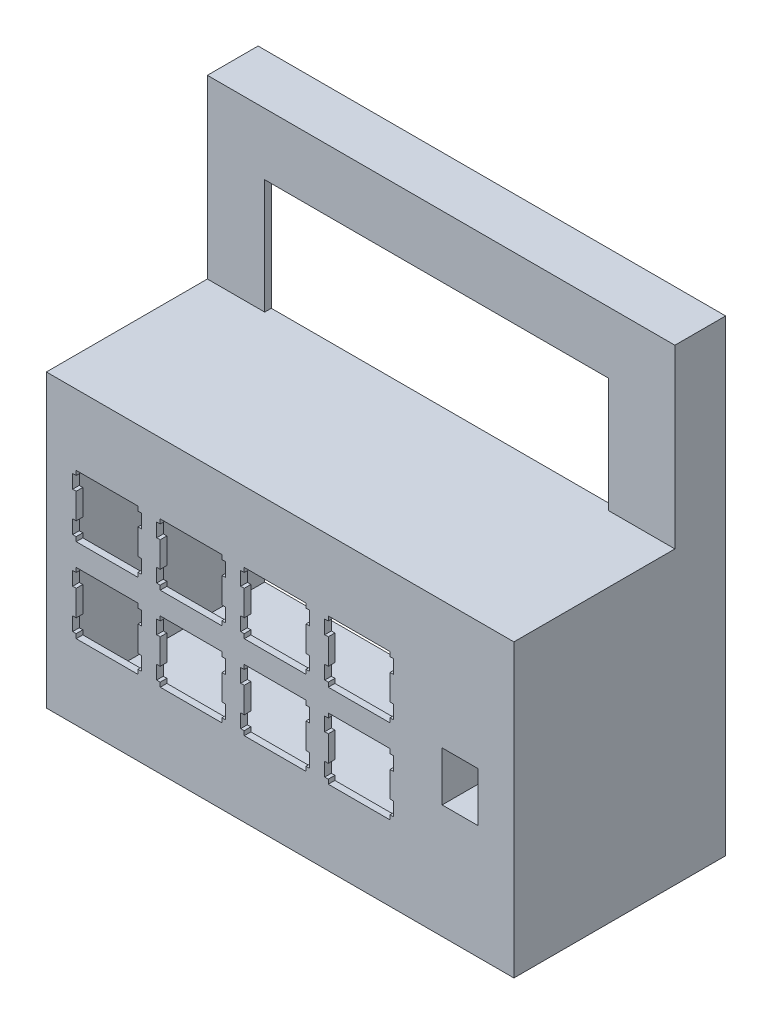
SolidWorks part; units mm, degrees
ref_plane "前视基准面" through (0, 0, 0) normal (0, 0, 1) x (1, 0, 0)
ref_plane "上视基准面" through (0, 0, 0) normal (0, 1, 0) x (1, 0, 0)
ref_plane "右视基准面" through (0, 0, 0) normal (1, 0, 0) x (0, 0, -1)
sketch "草图1" plane through (0, 0, 0) normal (0, 0, 1) x (1, 0, 0)
  line L11 (0, 0) -> (0, -40)
  line L12 (0, -40) -> (106, -40)
  line L13 (106, -40) -> (106, 0)
  line L14 (106, 0) -> (0, 0)
extrude "凸台-拉伸1" add sketch "草图1" along normal blind 1.5
sketch "草图5" plane through (0, -40, 0) normal (0, -1, 0) x (1, 0, 0)
  line L0 (0, 0) -> (106, 0)
  line L1 (106, 0) -> (106, 36.5)
  line L2 (106, 36.5) -> (0, 36.5)
  line L3 (0, 36.5) -> (0, 0)
extrude "凸台-拉伸4" add sketch "草图5" along normal blind 1.5
sketch "草图6" plane through (0, 0, 36.5) normal (0, 0, 1) x (1, 0, 0)
  line L0 (0, -40) -> (0, -106)
  line L1 (0, -106) -> (106, -106)
  line L2 (106, -106) -> (106, -40)
  line L3 (106, -40) -> (0, -40)
extrude "凸台-拉伸5" add sketch "草图6" along normal blind 1.5
sketch "草图7" plane through (0, 0, 0) normal (0, 0, -1) x (-1, 0, 0)
  line L0 (-106, -41.5) -> (-106, 0)
  line L1 (-106, 0) -> (0, 0)
  line L2 (0, 0) -> (0, -41.5)
  line L3 (0, -41.5) -> (-1.5, -41.5)
  line L4 (0, -41.5) -> (-106, -41.5) construction
  line L5 (-1.5, -41.5) -> (-1.5, -1.5)
  line L6 (-1.5, -1.5) -> (-104.5, -1.5)
  line L7 (-104.5, -1.5) -> (-104.5, -41.5)
  line L8 (-104.5, -41.5) -> (-106, -41.5)
extrude "凸台-拉伸6" add sketch "草图7" along normal blind 10
sketch "草图8" plane through (0, 0, 36.5) normal (0, 0, -1) x (-1, 0, 0)
  line L0 (-106, -41.5) -> (-106, -106)
  line L1 (-106, -106) -> (0, -106)
  line L2 (0, -106) -> (0, -41.5)
  line L3 (0, -41.5) -> (-1.5, -41.5)
  line L4 (-106, -41.5) -> (0, -41.5) construction
  line L5 (-1.5, -41.5) -> (-1.5, -104.5)
  line L6 (-1.5, -104.5) -> (-104.5, -104.5)
  line L7 (-104.5, -104.5) -> (-104.5, -41.5)
  line L8 (-104.5, -41.5) -> (-106, -41.5)
extrude "凸台-拉伸7" add sketch "草图8" along normal blind 46.5
sketch "草图11" plane through (0, 0, 38) normal (0, 0, 1) x (1, 0, 0)
  line L0 (63.9112, -74.9976) -> (63.9112, -75.9981)
  line L1 (63.9112, -75.9981) -> (63.1104, -75.9981)
  line L2 (63.1104, -75.9981) -> (63.1104, -79.0973)
  line L3 (63.1104, -79.0973) -> (63.9112, -79.0973)
  line L4 (63.9112, -79.0973) -> (63.9112, -84.8973)
  line L5 (63.9112, -84.8973) -> (63.1104, -84.8973)
  line L6 (63.1104, -84.8973) -> (63.1104, -87.9979)
  line L7 (63.1104, -87.9979) -> (63.9112, -87.9979)
  line L8 (63.9112, -87.9979) -> (63.9112, -88.9983)
  line L9 (63.9112, -88.9983) -> (77.9105, -88.9983)
  line L10 (77.9105, -88.9983) -> (77.9105, -87.9979)
  line L11 (77.9105, -87.9979) -> (78.7113, -87.9979)
  line L12 (78.7113, -87.9979) -> (78.7113, -84.8973)
  line L13 (78.7113, -84.8973) -> (77.9105, -84.8973)
  line L14 (77.9105, -84.8973) -> (77.9105, -79.0973)
  line L15 (77.9105, -79.0973) -> (78.7113, -79.0973)
  line L16 (78.7113, -79.0973) -> (78.7113, -75.9981)
  line L17 (78.7113, -75.9981) -> (77.9105, -75.9981)
  line L18 (77.9105, -75.9981) -> (77.9105, -74.9976)
  line L19 (77.9105, -74.9976) -> (63.9112, -74.9976)
  line L20 (44.8612, -74.9976) -> (44.8612, -75.9981)
  line L21 (44.8612, -75.9981) -> (44.0604, -75.9981)
  line L22 (44.0604, -75.9981) -> (44.0604, -79.0973)
  line L23 (44.0604, -79.0973) -> (44.8612, -79.0973)
  line L24 (44.8612, -79.0973) -> (44.8612, -84.8973)
  line L25 (44.8612, -84.8973) -> (44.0604, -84.8973)
  line L26 (44.0604, -84.8973) -> (44.0604, -87.9979)
  line L27 (44.0604, -87.9979) -> (44.8612, -87.9979)
  line L28 (44.8612, -87.9979) -> (44.8612, -88.9983)
  line L29 (44.8612, -88.9983) -> (58.8605, -88.9983)
  line L30 (58.8605, -88.9983) -> (58.8605, -87.9979)
  line L31 (58.8605, -87.9979) -> (59.6613, -87.9979)
  line L32 (59.6613, -87.9979) -> (59.6613, -84.8973)
  line L33 (59.6613, -84.8973) -> (58.8605, -84.8973)
  line L34 (58.8605, -84.8973) -> (58.8605, -79.0973)
  line L35 (58.8605, -79.0973) -> (59.6613, -79.0973)
  line L36 (59.6613, -79.0973) -> (59.6613, -75.9981)
  line L37 (59.6613, -75.9981) -> (58.8605, -75.9981)
  line L38 (58.8605, -75.9981) -> (58.8605, -74.9976)
  line L39 (58.8605, -74.9976) -> (44.8612, -74.9976)
  line L40 (25.8112, -74.9976) -> (25.8112, -75.9981)
  line L41 (25.8112, -75.9981) -> (25.0105, -75.9981)
  line L42 (25.0105, -75.9981) -> (25.0105, -79.0973)
  line L43 (25.0105, -79.0973) -> (25.8112, -79.0973)
  line L44 (25.8112, -79.0973) -> (25.8112, -84.8973)
  line L45 (25.8112, -84.8973) -> (25.0105, -84.8973)
  line L46 (25.0105, -84.8973) -> (25.0105, -87.9979)
  line L47 (25.0105, -87.9979) -> (25.8112, -87.9979)
  line L48 (25.8112, -87.9979) -> (25.8112, -88.9983)
  line L49 (25.8112, -88.9983) -> (39.8105, -88.9983)
  line L50 (39.8105, -88.9983) -> (39.8105, -87.9979)
  line L51 (39.8105, -87.9979) -> (40.6113, -87.9979)
  line L52 (40.6113, -87.9979) -> (40.6113, -84.8973)
  line L53 (40.6113, -84.8973) -> (39.8105, -84.8973)
  line L54 (39.8105, -84.8973) -> (39.8105, -79.0973)
  line L55 (39.8105, -79.0973) -> (40.6113, -79.0973)
  line L56 (40.6113, -79.0973) -> (40.6113, -75.9981)
  line L57 (40.6113, -75.9981) -> (39.8105, -75.9981)
  line L58 (39.8105, -75.9981) -> (39.8105, -74.9976)
  line L59 (39.8105, -74.9976) -> (25.8112, -74.9976)
  line L60 (6.7612, -74.9976) -> (6.7612, -75.9981)
  line L61 (6.7612, -75.9981) -> (5.9605, -75.9981)
  line L62 (5.9605, -75.9981) -> (5.9605, -79.0973)
  line L63 (5.9605, -79.0973) -> (6.7612, -79.0973)
  line L64 (6.7612, -79.0973) -> (6.7612, -84.8973)
  line L65 (6.7612, -84.8973) -> (5.9605, -84.8973)
  line L66 (5.9605, -84.8973) -> (5.9605, -87.9979)
  line L67 (5.9605, -87.9979) -> (6.7612, -87.9979)
  line L68 (6.7612, -87.9979) -> (6.7612, -88.9983)
  line L69 (6.7612, -88.9983) -> (20.7607, -88.9983)
  line L70 (20.7607, -88.9983) -> (20.7607, -87.9979)
  line L71 (20.7607, -87.9979) -> (21.5613, -87.9979)
  line L72 (21.5613, -87.9979) -> (21.5613, -84.8973)
  line L73 (21.5613, -84.8973) -> (20.7607, -84.8973)
  line L74 (20.7607, -84.8973) -> (20.7607, -79.0973)
  line L75 (20.7607, -79.0973) -> (21.5613, -79.0973)
  line L76 (21.5613, -79.0973) -> (21.5613, -75.9981)
  line L77 (21.5613, -75.9981) -> (20.7607, -75.9981)
  line L78 (20.7607, -75.9981) -> (20.7607, -74.9976)
  line L79 (20.7607, -74.9976) -> (6.7612, -74.9976)
  line L80 (63.9112, -55.949) -> (63.9112, -56.9495)
  line L81 (63.9112, -56.9495) -> (63.1104, -56.9495)
  line L82 (63.1104, -56.9495) -> (63.1104, -60.0487)
  line L83 (63.1104, -60.0487) -> (63.9112, -60.0487)
  line L84 (63.9112, -60.0487) -> (63.9112, -65.8487)
  line L85 (63.9112, -65.8487) -> (63.1104, -65.8487)
  line L86 (63.1104, -65.8487) -> (63.1104, -68.9493)
  line L87 (63.1104, -68.9493) -> (63.9112, -68.9493)
  line L88 (63.9112, -68.9493) -> (63.9112, -69.9483)
  line L89 (63.9112, -69.9483) -> (77.9105, -69.9483)
  line L90 (77.9105, -69.9483) -> (77.9105, -68.9493)
  line L91 (77.9105, -68.9493) -> (78.7113, -68.9493)
  line L92 (78.7113, -68.9493) -> (78.7113, -65.8487)
  line L93 (78.7113, -65.8487) -> (77.9105, -65.8487)
  line L94 (77.9105, -65.8487) -> (77.9105, -60.0487)
  line L95 (77.9105, -60.0487) -> (78.7113, -60.0487)
  line L96 (78.7113, -60.0487) -> (78.7113, -56.9495)
  line L97 (78.7113, -56.9495) -> (77.9105, -56.9495)
  line L98 (77.9105, -56.9495) -> (77.9105, -55.949)
  line L99 (77.9105, -55.949) -> (63.9112, -55.949)
  line L100 (44.8612, -55.949) -> (44.8612, -56.9495)
  line L101 (44.8612, -56.9495) -> (44.0604, -56.9495)
  line L102 (44.0604, -56.9495) -> (44.0604, -60.0487)
  line L103 (44.0604, -60.0487) -> (44.8612, -60.0487)
  line L104 (44.8612, -60.0487) -> (44.8612, -65.8487)
  line L105 (44.8612, -65.8487) -> (44.0604, -65.8487)
  line L106 (44.0604, -65.8487) -> (44.0604, -68.9493)
  line L107 (44.0604, -68.9493) -> (44.8612, -68.9493)
  line L108 (44.8612, -68.9493) -> (44.8612, -69.9483)
  line L109 (44.8612, -69.9483) -> (58.8605, -69.9483)
  line L110 (58.8605, -69.9483) -> (58.8605, -68.9493)
  line L111 (58.8605, -68.9493) -> (59.6613, -68.9493)
  line L112 (59.6613, -68.9493) -> (59.6613, -65.8487)
  line L113 (59.6613, -65.8487) -> (58.8605, -65.8487)
  line L114 (58.8605, -65.8487) -> (58.8605, -60.0487)
  line L115 (58.8605, -60.0487) -> (59.6613, -60.0487)
  line L116 (59.6613, -60.0487) -> (59.6613, -56.9495)
  line L117 (59.6613, -56.9495) -> (58.8605, -56.9495)
  line L118 (58.8605, -56.9495) -> (58.8605, -55.949)
  line L119 (58.8605, -55.949) -> (44.8612, -55.949)
  line L120 (25.8112, -55.949) -> (25.8112, -56.9495)
  line L121 (25.8112, -56.9495) -> (25.0105, -56.9495)
  line L122 (25.0105, -56.9495) -> (25.0105, -60.0487)
  line L123 (25.0105, -60.0487) -> (25.8112, -60.0487)
  line L124 (25.8112, -60.0487) -> (25.8112, -65.8487)
  line L125 (25.8112, -65.8487) -> (25.0105, -65.8487)
  line L126 (25.0105, -65.8487) -> (25.0105, -68.9493)
  line L127 (25.0105, -68.9493) -> (25.8112, -68.9493)
  line L128 (25.8112, -68.9493) -> (25.8112, -69.9483)
  line L129 (25.8112, -69.9483) -> (39.8105, -69.9483)
  line L130 (39.8105, -69.9483) -> (39.8105, -68.9493)
  line L131 (39.8105, -68.9493) -> (40.6113, -68.9493)
  line L132 (40.6113, -68.9493) -> (40.6113, -65.8487)
  line L133 (40.6113, -65.8487) -> (39.8105, -65.8487)
  line L134 (39.8105, -65.8487) -> (39.8105, -60.0487)
  line L135 (39.8105, -60.0487) -> (40.6113, -60.0487)
  line L136 (40.6113, -60.0487) -> (40.6113, -56.9495)
  line L137 (40.6113, -56.9495) -> (39.8105, -56.9495)
  line L138 (39.8105, -56.9495) -> (39.8105, -55.949)
  line L139 (39.8105, -55.949) -> (25.8112, -55.949)
  line L140 (6.7612, -55.949) -> (6.7612, -56.9495)
  line L141 (6.7612, -56.9495) -> (5.9605, -56.9495)
  line L142 (5.9605, -56.9495) -> (5.9605, -60.0487)
  line L143 (5.9605, -60.0487) -> (6.7612, -60.0487)
  line L144 (6.7612, -60.0487) -> (6.7612, -65.8487)
  line L145 (6.7612, -65.8487) -> (5.9605, -65.8487)
  line L146 (5.9605, -65.8487) -> (5.9605, -68.9493)
  line L147 (5.9605, -68.9493) -> (6.7612, -68.9493)
  line L148 (6.7612, -68.9493) -> (6.7612, -69.9483)
  line L149 (6.7612, -69.9483) -> (20.7607, -69.9483)
  line L150 (20.7607, -69.9483) -> (20.7607, -68.9493)
  line L151 (20.7607, -68.9493) -> (21.5613, -68.9493)
  line L152 (21.5613, -68.9493) -> (21.5613, -65.8487)
  line L153 (21.5613, -65.8487) -> (20.7607, -65.8487)
  line L154 (20.7607, -65.8487) -> (20.7607, -60.0487)
  line L155 (20.7607, -60.0487) -> (21.5613, -60.0487)
  line L156 (21.5613, -60.0487) -> (21.5613, -56.9495)
  line L157 (21.5613, -56.9495) -> (20.7607, -56.9495)
  line L158 (20.7607, -56.9495) -> (20.7607, -55.949)
  line L159 (20.7607, -55.949) -> (6.7612, -55.949)
  line L160 (89.7351, -68.9493) -> (97.8351, -68.9493)
  line L161 (97.8351, -68.9493) -> (97.8351, -80.1493)
  line L162 (97.8351, -80.1493) -> (89.7351, -80.1493)
  line L163 (89.7351, -80.1493) -> (89.7351, -68.9493)
extrude "切除-拉伸1" cut sketch "草图11" against normal blind 1.5
sketch "草图12" plane through (0, 0, 36.5) normal (0, 0, -1) x (-1, 0, 0)
  line L0 (-99.3351, -67.4493) -> (-88.2351, -67.4493)
  line L2 (-88.2351, -67.4493) -> (-88.2351, -81.6493)
  line L3 (-88.2351, -81.6493) -> (-99.3351, -81.6493)
  line L4 (-99.3351, -81.6493) -> (-99.3351, -67.4493)
  line L6 (-97.8351, -68.9493) -> (-89.7351, -68.9493)
  line L7 (-97.8351, -68.9493) -> (-89.7351, -68.9493) construction
  line L8 (-89.7351, -68.9493) -> (-89.7351, -80.1493)
  line L9 (-89.7351, -80.1493) -> (-97.8351, -80.1493)
  line L10 (-97.8351, -80.1493) -> (-97.8351, -68.9493)
extrude "凸台-拉伸8" add sketch "草图12" along normal blind 10
sketch "草图13" plane through (0, 0, 1.5) normal (0, 0, 1) x (1, 0, 0)
  line L3 (13, -14) -> (13, -40)
  line L4 (0, -40) -> (106, -40) construction
  line L7 (91, -14) -> (91, -40)
  line L8 (91, -40) -> (13, -40)
  line L9 (13, -14) -> (91, -14)
extrude "切除-拉伸2" cut sketch "草图13" against normal blind 1.5
